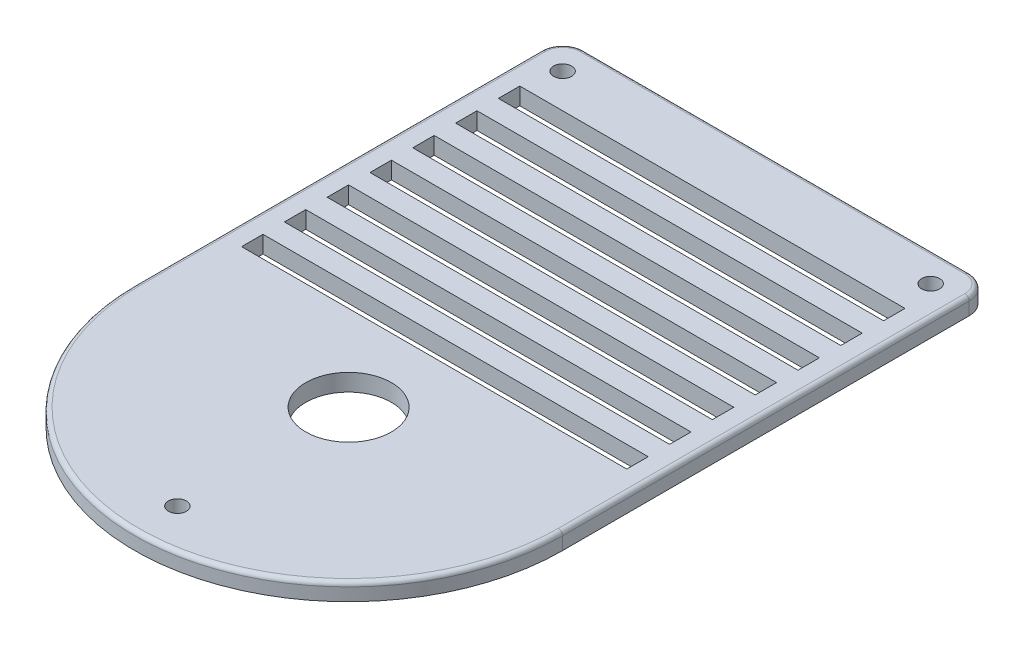
SolidWorks part; units mm, degrees
ref_plane "前视基准面" through (0, 0, 0) normal (0, 0, 1) x (1, 0, 0)
ref_plane "上视基准面" through (0, 0, 0) normal (0, 1, 0) x (1, 0, 0)
ref_plane "右视基准面" through (0, 0, 0) normal (1, 0, 0) x (0, 0, -1)
sketch "草图2" plane through (0, 0, 0) normal (0, 1, 0) x (1, 0, 0)
  line L0 (-50, -50) -> (-50, 50)
  line L1 (-50, 50) -> (50, 50)
  line L2 (50, -50) -> (50, 50)
  line L3 (-50, -50) -> (50, 50) construction
  line L4 (-50, 50) -> (50, -50) construction
  arc A0 (-50, -50) -> (50, -50) centre (0, -50) ccw
  point P0 (0, 0)
  dimension "D3" = 50
  dimension "D1" = 100
  dimension "D2" = 100
extrude "凸台-拉伸1" add sketch "草图2" along normal blind 4
sketch "草图3" plane through (0, 0, 0) normal (0, -1, 0) x (1, 0, 0)
  circle A0 centre (0, 90) radius 2.1
  circle A2 centre (43, -43) radius 2.1
  circle A3 centre (-43, -43) radius 2.1
  dimension "D1" = 4.2
  dimension "D2" = 4.2
  dimension "D3" = 4.2
extrude "切除-拉伸1" cut sketch "草图3" against normal blind 4
sketch "草图4" plane through (0, 4, 0) normal (0, 1, 0) x (1, 0, 0)
  circle A0 centre (0, -50) radius 10
  dimension "D1" = 20
extrude "切除-拉伸2" cut sketch "草图4" against normal blind 4
sketch "草图5" plane through (0, 4, 0) normal (0, 1, 0) x (1, 0, 0)
  line L0 (50, 50) -> (-50, 50) construction
  line L1 (-45, 35) -> (45, 35)
  line L2 (-45, 35) -> (-45, 30)
  line L3 (-45, 30) -> (45, 30)
  line L4 (45, 35) -> (45, 30)
  line L5 (50, -50) -> (50, 50) construction
  line L6 (-50, 50) -> (-50, -50) construction
  line L7 (-45, 25) -> (-45, 20)
  line L8 (-45, 25) -> (45, 25)
  line L9 (45, 25) -> (45, 20)
  line L10 (-45, 20) -> (45, 20)
  line L11 (-45, 15) -> (-45, 10)
  line L12 (-45, 15) -> (45, 15)
  line L13 (45, 15) -> (45, 10)
  line L14 (-45, 10) -> (45, 10)
  line L15 (-45, 5) -> (-45, 0)
  line L16 (-45, 5) -> (45, 5)
  line L17 (45, 5) -> (45, 0)
  line L18 (-45, 0) -> (45, 0)
  line L19 (-45, -5) -> (-45, -10)
  line L20 (-45, -5) -> (45, -5)
  line L21 (45, -5) -> (45, -10)
  line L22 (-45, -10) -> (45, -10)
  line L23 (-45, -15) -> (-45, -20)
  line L24 (-45, -15) -> (45, -15)
  line L25 (45, -15) -> (45, -20)
  line L26 (-45, -20) -> (45, -20)
  line L27 (-45, -25) -> (-45, -30)
  line L28 (-45, -25) -> (45, -25)
  line L29 (45, -25) -> (45, -30)
  line L30 (-45, -30) -> (45, -30)
  dimension "D1" = 15
  dimension "D2" = 5
  dimension "D3" = 5
  dimension "D4" = 5
  dimension "D5" = 7
extrude "切除-拉伸3" cut sketch "草图5" against normal blind 5
fillet "圆角1" radius 5 2 edges at (50, 2, -50) (-50, 2, -50)
fillet "圆角2" radius 1 6 edges at (48.5355, 4, -48.5355) (50, 4, 2.5) (0, 4, 100) (-50, 4, 2.5) (-48.5355, 4, -48.5355) (0, 4, -50)
